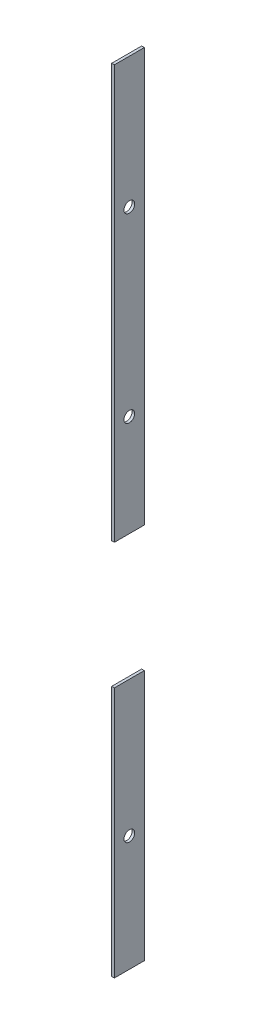
SolidWorks part; units mm, degrees
material "Custom Plastic"
ref_plane "X-Y Datum" through (0, 0, 0) normal (0, 0, 1) x (1, 0, 0)
ref_plane "X-Z Datum" through (0, 0, 0) normal (0, 1, 0) x (1, 0, 0)
ref_plane "Y-Z Datum" through (0, 0, 0) normal (1, 0, 0) x (0, 0, -1)
sketch "Sketch1" plane through (0, 0, 0) normal (1, 0, 0) x (0, 0, -1)
  line L4 (-318.4298, -78.5159) -> (-335.1438, -78.5159)
  line L5 (-335.1438, -78.5159) -> (-335.1438, -219.1349)
  line L6 (-335.1438, -219.1349) -> (-318.4298, -219.1349)
  line L7 (-318.4298, -219.1349) -> (-318.4298, -78.5159)
  line L8 (-318.4298, -78.5159) -> (-335.1438, -78.5159)
  line L9 (-335.1438, -78.5159) -> (-335.1438, -219.1349)
  line L10 (-335.1438, -219.1349) -> (-318.4298, -219.1349)
  line L11 (-318.4298, -219.1349) -> (-318.4298, -78.5159)
  line L12 (-335.1438, -7.9909) -> (-318.4298, -7.9909)
  line L13 (-318.4298, -7.9909) -> (-318.4298, 223.4302)
  line L14 (-318.4298, 223.4302) -> (-335.1438, 223.4302)
  line L15 (-335.1438, 223.4302) -> (-335.1438, -7.9909)
  line L16 (-335.1438, -7.9909) -> (-318.4298, -7.9909)
  line L17 (-318.4298, -7.9909) -> (-318.4298, 223.4302)
  line L18 (-318.4298, 223.4302) -> (-335.1438, 223.4302)
  line L19 (-335.1438, 223.4302) -> (-335.1438, -7.9909)
  circle A0 centre (-326.7868, 150.3576) radius 3
  circle A1 centre (-326.7868, 48.7576) radius 3
  circle A2 centre (-326.7868, -154.4424) radius 3
  point P6 (-326.7868, -154.4424)
  point P8 (-326.7868, 48.7576)
  point P10 (-326.7868, 150.3576)
  dimension "D3" = 6
  dimension "D1" = 0
  dimension "D2" = 0
extrude "Boss-Extrude1" add sketch "Sketch1" along normal blind 1.5
other "Save Bodies1"
